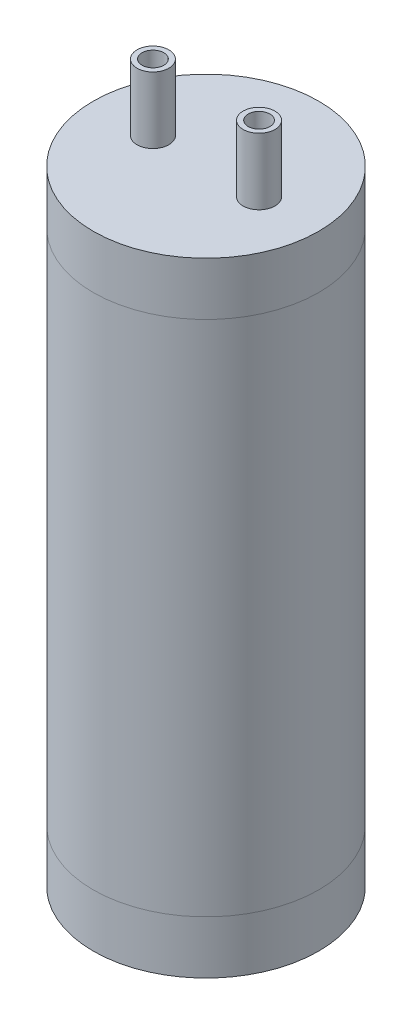
SolidWorks part; units mm, degrees
ref_plane "Front Plane" through (0, 0, 0) normal (0, 0, 1) x (1, 0, 0)
ref_plane "Top Plane" through (0, 0, 0) normal (0, 1, 0) x (1, 0, 0)
ref_plane "Right Plane" through (0, 0, 0) normal (1, 0, 0) x (0, 0, -1)
sketch "Sketch1" plane through (0, 0, 0) normal (0, 1, 0) x (1, 0, 0)
  circle A0 centre (0, 0) radius 42.5
extrude "Vessel_D85_catalogue" add sketch "Sketch1" along normal blind 195 from offset 20 separate body
sketch "Sketch2" plane through (0, 0, 0) normal (0, 1, 0) x (1, 0, 0)
  circle A0 centre (0, 0) radius 42.5
extrude "Bottom_head_envelope" add sketch "Sketch2" against normal blind 20 from offset 20 separate body
sketch "Sketch3" plane through (0, 0, 0) normal (0, 1, 0) x (1, 0, 0)
  circle A0 centre (0, 0) radius 42.5
extrude "Top_head_envelope" add sketch "Sketch3" along normal blind 20 from offset 215 separate body
sketch "Sketch4" plane through (0, 0, 0) normal (0, 1, 0) x (1, 0, 0)
  circle A0 centre (0, 0) radius 4
extrude "M8_mount_stud_length_assumed" add sketch "Sketch4" against normal blind 8 from offset 0 separate body
sketch "Sketch5" plane through (0, 0, 0) normal (0, 1, 0) x (1, 0, 0)
  circle A0 centre (-20, 0) radius 6
  circle A1 centre (-20, 0) radius 4.1
extrude "Inlet_ODS8_provisional_position" add sketch "Sketch5" along normal blind 25 from offset 235 separate body
sketch "Sketch6" plane through (0, 0, 0) normal (0, 1, 0) x (1, 0, 0)
  circle A0 centre (20, 0) radius 6
  circle A1 centre (20, 0) radius 4.1
extrude "Liquid_outlet_dip_tube_required_ODS8_provisional_position" add sketch "Sketch6" along normal blind 25 from offset 235 separate body
